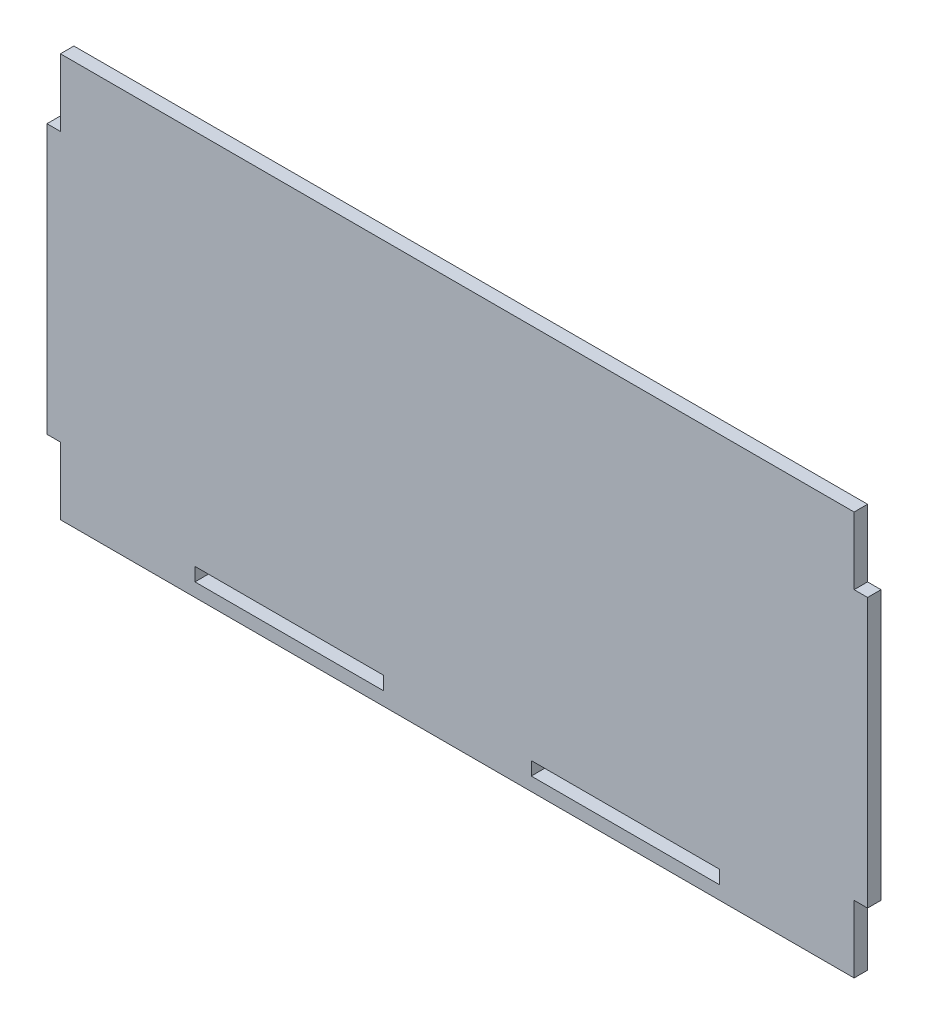
SolidWorks part; units mm, degrees
ref_plane "Front Plane" through (0, 0, 0) normal (0, 0, 1) x (1, 0, 0)
ref_plane "Top Plane" through (0, 0, 0) normal (0, 1, 0) x (1, 0, 0)
ref_plane "Right Plane" through (0, 0, 0) normal (1, 0, 0) x (0, 0, -1)
sketch "Sketch1" plane through (0, 0, 0) normal (0, 0, 1) x (1, 0, 0)
  line L0 (-147.5, 150) -> (-147.5, 177.0439) construction
  line L1 (0, 0) -> (-295, 0)
  line L2 (0, 0) -> (0, 150)
  line L3 (0, 150) -> (-295, 150)
  line L4 (-295, 0) -> (-295, 150)
  line L5 (-295, 125) -> (-300, 125)
  line L6 (-295, 125) -> (-295, 25)
  line L7 (-295, 25) -> (-300, 25)
  line L8 (-300, 125) -> (-300, 25)
  line L9 (0, 25) -> (5, 25)
  line L10 (5, 125) -> (5, 25)
  line L11 (0, 125) -> (5, 125)
  line L12 (0, 125) -> (0, 25)
  dimension "D1" = 295
  dimension "D2" = 150
  dimension "D3" = 100
  dimension "D4" = 5
  dimension "D5" = 25
extrude "Boss-Extrude1" add sketch "Sketch1" along normal blind 5 contours L5 L8 L7 L4 | L4 L1 L2 L3 | L11 L2 L9 L10
sketch "Sketch2" plane through (0, 0, 5) normal (0, 0, 1) x (1, 0, 0)
  line L0 (0, 0) -> (-295, 0) construction
  line L1 (-245, 5) -> (-175, 5)
  line L2 (-245, 5) -> (-245, 10)
  line L3 (-245, 10) -> (-175, 10)
  line L4 (-175, 5) -> (-175, 10)
  line L5 (-295, 0) -> (-295, 25) construction
  line L6 (-147.5, 150) -> (-147.5, 83.9383) construction
  line L7 (0, 150) -> (-295, 150) construction
  line L8 (-120, 5) -> (-120, 10)
  line L9 (-50, 10) -> (-120, 10)
  line L10 (-50, 5) -> (-50, 10)
  line L11 (-50, 5) -> (-120, 5)
  dimension "D1" = 70
  dimension "D2" = 5
  dimension "D3" = 5
  dimension "D4" = 50
extrude "Cut-Extrude1" cut sketch "Sketch2" against normal blind 5
